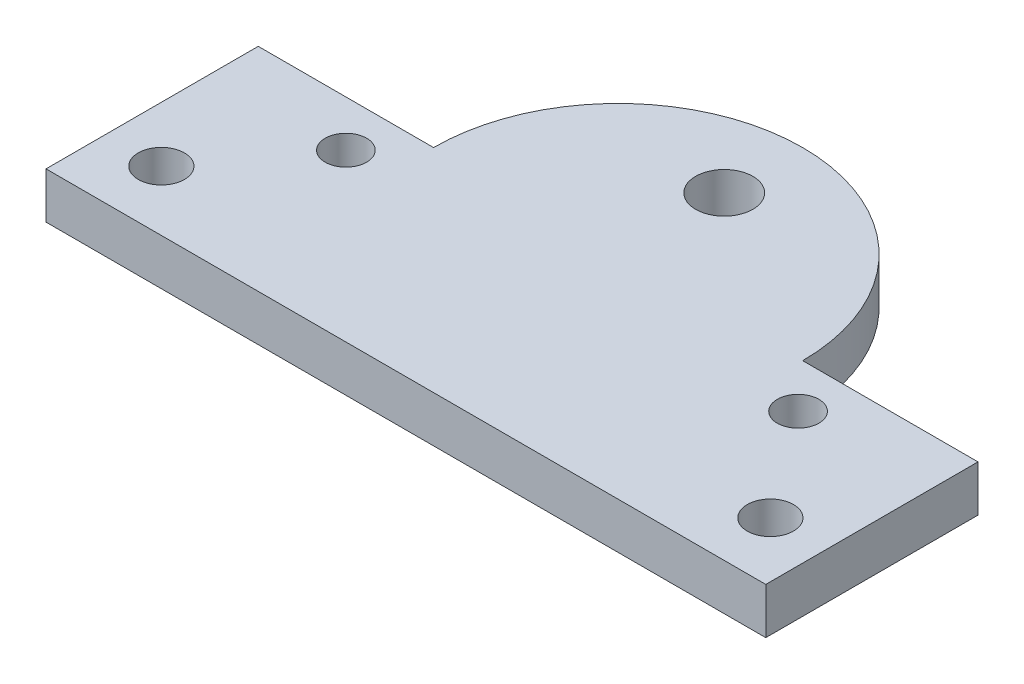
SolidWorks part; units mm, degrees
ref_plane "Ön Düzlem" through (0, 0, 0) normal (0, 0, 1) x (1, 0, 0)
ref_plane "Üst Düzlem" through (0, 0, 0) normal (0, 1, 0) x (1, 0, 0)
ref_plane "Sağ Düzlem" through (0, 0, 0) normal (1, 0, 0) x (0, 0, -1)
sketch "Çizim1" plane through (0, 0, 0) normal (0, 1, 0) x (1, 0, 0)
  line L1 (-39, 11.5) -> (-20, 11.5)
  line L2 (-39, 11.5) -> (-39, -11.5)
  line L3 (-39, -11.5) -> (39, -11.5)
  line L4 (39, 11.5) -> (39, -11.5)
  line L8 (20, 11.5) -> (39, 11.5)
  circle A0 centre (0, 23) radius 3.1
  arc A1 (20, 11.5) -> (-20, 11.5) centre (0, 11.5) ccw
  circle A2 centre (-24.5, 6.5) radius 2.25
  circle A3 centre (-33, -5) radius 2.5
  circle A4 centre (33, -5) radius 2.5
  circle A5 centre (24.5, 6.5) radius 2.25
  point P0 (0, 0)
  dimension "D1" = 6.5
  dimension "D8" = 20
  dimension "D2" = 6
  dimension "D3" = 66
  dimension "D4" = 49
  dimension "D5" = 28
  dimension "D6" = 18
  dimension "D7" = 14.5
  dimension "D9" = 5
extrude "Yükseklik-Ekstrüzyon1" add sketch "Çizim1" along normal blind 5
